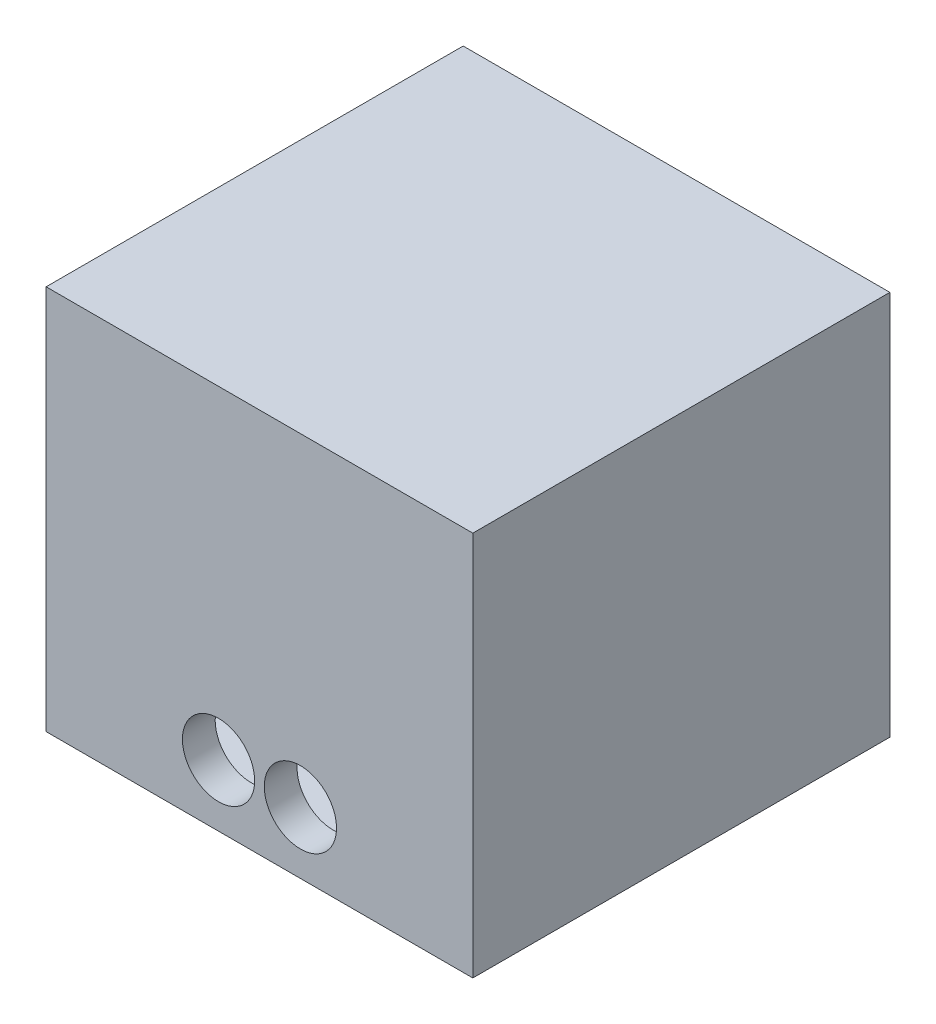
SolidWorks part; units mm, degrees
ref_plane "Front Plane" through (0, 0, 0) normal (0, 0, 1) x (1, 0, 0)
ref_plane "Top Plane" through (0, 0, 0) normal (0, 1, 0) x (1, 0, 0)
ref_plane "Right Plane" through (0, 0, 0) normal (1, 0, 0) x (0, 0, -1)
ref_plane "Plane1" through (0, 0, 433) normal (0, 0, 1) x (1, 0, 0)
sketch "Sketch1" plane through (0, 0, 433) normal (0, 0, 1) x (1, 0, 0)
  line L0 (-443, 782) -> (-443, -18)
  line L1 (-443, -18) -> (443, -18)
  line L2 (443, -18) -> (443, 782)
  line L3 (443, 782) -> (-443, 782)
  dimension "D1" = 800
extrude "Boss-Extrude1" add sketch "Sketch1" against normal blind 866
ref_plane "Plane2" through (-425, 0, 0) normal (-1, 0, 0) x (0, -1, 0)
sketch "Sketch2" plane through (-425, 0, 0) normal (-1, 0, 0) x (0, -1, 0)
  line L0 (-7, -415) -> (-7, 415)
  line L1 (-7, 415) -> (-757, 415)
  line L2 (-757, 415) -> (-757, -415)
  line L3 (-757, -415) -> (-7, -415)
  dimension "D1" = 750
extrude "Cut-Extrude1" cut sketch "Sketch2" against normal blind 850
sketch "Sketch3" plane through (0, 0, -433) normal (0, 0, -1) x (-1, 0, 0)
  line L0 (-300, 725) -> (-300, 715)
  line L1 (-285, 700) -> (285, 700)
  line L2 (300, 715) -> (300, 725)
  line L3 (285, 740) -> (-285, 740)
  arc A0 (-300, 715) -> (-285, 700) centre (-285, 715) ccw
  arc A1 (285, 700) -> (300, 715) centre (285, 715) ccw
  arc A2 (300, 725) -> (285, 740) centre (285, 725) ccw
  arc A3 (-285, 740) -> (-300, 725) centre (-285, 725) ccw
  dimension "D1" = 700
extrude "Cut-Extrude2" cut sketch "Sketch3" against normal blind 288
sketch "Sketch4" plane through (0, 0, 415) normal (0, 0, -1) x (-1, 0, 0)
  arc A0 (0, 80.4196) -> (0, 139.5804) centre (-85, 110) cw
  arc A1 (0, 139.5804) -> (0, 80.4196) centre (85, 110) cw
extrude "Boss-Extrude2" add sketch "Sketch4" along normal blind 50
hole_wizard "Hole1" positions "Sketch6" profile "Sketch5" legacy
sketch "Sketch6" plane through (0, 0, 365) normal (0, 0, -1) x (-1, 0, 0)
  point P0 (-85, 110)
  point P1 (85, 110)
sketch "Sketch5" plane through (85, 110, 365) normal (1, 0, 0) x (0, 1, 0)
  line L0 (0, 0) -> (0, 68)
  line L1 (0, 68) -> (75, 68)
  line L2 (75, 68) -> (75, 0)
  line L3 (75, 0) -> (0, 0)
  line L4 (0, 110) -> (0, -10) construction
  dimension "Diameter" = 150
  dimension "Depth" = 68
equation "\"box_height\" = 800mm"
equation "\"D1@Sketch1\"=\"box_height\""
equation "\"D1@Sketch3\"=\"box_height\" - 100mm"
equation "\"D1@Sketch2\"=\"box_height\" - 50mm"
